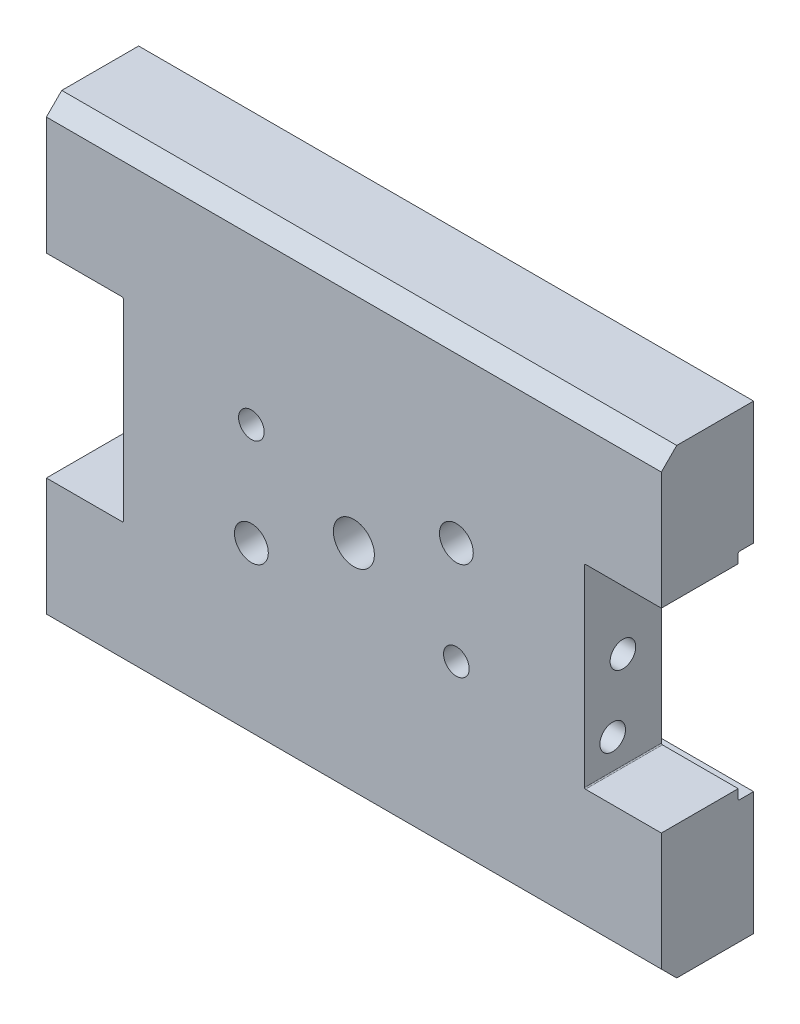
SolidWorks part; units mm, degrees
ref_plane "Piano frontale" through (0, 0, 0) normal (0, 0, 1) x (1, 0, 0)
ref_plane "Piano superiore" through (0, 0, 0) normal (0, 1, 0) x (1, 0, 0)
ref_plane "Piano destro" through (0, 0, 0) normal (1, 0, 0) x (0, 0, -1)
sketch "Schizzo1" plane through (0, 0, 0) normal (0, 0, 1) x (1, 0, 0)
  line L12 (0, 0) -> (0, 62.9746) construction
  line L13 (0, 0) -> (63.3499, 0) construction
  line L14 (-60, 45) -> (60, 45)
  line L15 (60, 45) -> (60, 19)
  line L16 (60, 19) -> (45, 19)
  line L17 (45, 19) -> (45, -19)
  line L18 (45, -19) -> (60, -19)
  line L19 (60, -19) -> (60, -45)
  line L20 (60, -45) -> (-60, -45)
  line L21 (-60, -45) -> (-60, -19)
  line L22 (-60, -19) -> (-45, -19)
  line L23 (-45, -19) -> (-45, 19)
  line L24 (-45, 19) -> (-60, 19)
  line L25 (-60, 19) -> (-60, 45)
  line L26 (-60, 19) -> (-60, -19) construction
  line L27 (60, 19) -> (60, -19) construction
  line L28 (-45, 19) -> (45, 19) construction
  line L29 (-45, -19) -> (45, -19) construction
  dimension "D1" = 120
  dimension "D2" = 90
  dimension "D3" = 38
  dimension "D4" = 90
extrude "Estrusione-Estrusione1" add sketch "Schizzo1" along normal blind 18 contours L22 L23 L24 L25 L14 L15 L16 L17 L18 L19 L20 L21
sketch "Schizzo2" plane through (0, 0, 0) normal (1, 0, 0) x (0, 0, -1)
  line L0 (0, 19) -> (0, -19) construction
  line L1 (0, -21) -> (-3, -21)
  line L2 (0, -21) -> (0, 21)
  line L3 (0, 21) -> (-3, 21)
  line L4 (-3, -21) -> (-3, 21)
  line L5 (0, 0) -> (-50.4811, 0) construction
  dimension "D1" = 3
  dimension "D2" = 42
extrude "Taglio-Estrusione1" cut sketch "Schizzo2" against normal through all and the other way through all
hole_wizard "Foro filettato M6-1" positions "Schizzo3" profile "Schizzo4" tap size "M6" standard "ISO"
sketch "Schizzo3" plane through (45, 0, 0) normal (1, 0, 0) x (0, 0, -1)
  line L0 (-18, -19) -> (-3, 19) construction
  point P0 (-10.5, 0)
cosmetic thread "Filettatura del foro1" parameters "D1"=15, "D2"=6
sketch "Schizzo4" plane through (45, 0, 10.5) normal (0, 1, 0) x (0, 0, -1)
  line L0 (0, 0) -> (0, 21.5022)
  line L1 (0, 21.5022) -> (2.5, 20)
  line L2 (2.5, 20) -> (2.5, 0)
  line L5 (2.5, 0) -> (0, 0)
  line L10 (0, 21.5022) -> (-2.5, 20) construction
  line L11 (0, -6.35) -> (0, 107.95) construction
  dimension "Tap Drill Dia." = 5
  dimension "Tap Drill Depth" = 20
  dimension "Drill Angle" = 118
hole_wizard "Foro Ø8.0 (8)-1" positions "Schizzo5" profile "Schizzo6" hole size "Ø8.0" standard "ISO" end condition through all
sketch "Schizzo5" plane through (0, 0, 18) normal (0, 0, 1) x (1, 0, 0)
  line L0 (45, 0) -> (-45, 0) construction
  line L1 (45, 19) -> (45, -19) construction
  line L2 (-45, -19) -> (-45, 19) construction
  line L4 (0, -45) -> (0, 45) construction
  line L5 (60, -45) -> (-60, -45) construction
  line L6 (-60, 45) -> (60, 45) construction
  point P21 (0, 0)
sketch "Schizzo6" plane through (0, 0, 18) normal (1, 0, 0) x (0, -1, 0)
  line L0 (0, 0) -> (0, 18)
  line L1 (0, 18) -> (4, 18)
  line L2 (4, 18) -> (4, 0)
  line L5 (4, 0) -> (0, 0)
  line L11 (0, -6.35) -> (0, 107.95) construction
  dimension "Thru Hole Dia." = 8
  dimension "Thru Hole Depth" = 18
hole_wizard "Foro Ø5.0 (5)-2" positions "Schizzo7" profile "Schizzo8" hole size "Ø5.0" standard "ISO" end condition through all
sketch "Schizzo7" plane through (0, 0, 18) normal (0, 0, 1) x (1, 0, 0)
  line L0 (20, -10) -> (-20, 10) construction
  line L2 (0, 0) -> (0, 14.5749) construction
  point P0 (20, -10)
  point P2 (-20, 10)
  dimension "D1" = 10
  dimension "D2" = 20
sketch "Schizzo8" plane through (20, -10, 18) normal (1, 0, 0) x (0, -1, 0)
  line L0 (0, 0) -> (0, 18)
  line L1 (0, 18) -> (2.5, 18)
  line L2 (2.5, 18) -> (2.5, 0)
  line L5 (2.5, 0) -> (0, 0)
  line L11 (0, -6.35) -> (0, 107.95) construction
  dimension "Thru Hole Dia." = 5
  dimension "Thru Hole Depth" = 18
hole_wizard "Foro lamato per Vite M6 a testa cilindrica-1" positions "Schizzo9" profile "Schizzo10" counterbore size "M6" standard "ISO" end condition through all
sketch "Schizzo9" plane through (0, 0, 3) normal (0, 0, -1) x (-1, 0, 0)
  line L2 (-20, -10) -> (20, -10) construction
  line L3 (-20, -10) -> (-20, 10) construction
  line L4 (-20, 10) -> (20, 10) construction
  line L5 (20, -10) -> (20, 10) construction
  point P0 (-20, 10)
  point P2 (20, -10)
sketch "Schizzo10" plane through (20, 10, 3) normal (1, 0, 0) x (0, 1, 0)
  line L0 (0, 0) -> (0, 15)
  line L1 (0, 15) -> (3.3, 15)
  line L3 (3.3, 15) -> (3.3, 6.4)
  line L4 (3.3, 6.4) -> (5.5, 6.4)
  line L5 (5.5, 6.4) -> (5.5, 0)
  line L7 (5.5, 0) -> (0, 0)
  line L11 (0, -6.35) -> (0, 107.95) construction
  dimension "Thru Hole Dia." = 6.6
  dimension "Thru Hole Depth" = 15
  dimension "C'Bore Dia." = 11
  dimension "C'Bore Depth" = 6.4
hole_wizard "Foro Ø5.0 (5)-3" positions "Schizzo13" profile "Schizzo14" hole size "Ø5.0" standard "ISO"
sketch "Schizzo13" plane through (45, 0, 0) normal (1, 0, 0) x (0, 0, -1)
  line L0 (-12.5, -13) -> (-8.5, 13) construction
  line L2 (-10.5, 0) -> (-4.8871, 0) construction
  point P0 (-12.5, -13)
  point P2 (-8.5, 13)
  dimension "D1" = 13
  dimension "D2" = 2
sketch "Schizzo14" plane through (45, -13, 12.5) normal (0, 1, 0) x (0, 0, -1)
  line L0 (0, 0) -> (0, 11.5022)
  line L1 (0, 11.5022) -> (2.5, 10)
  line L2 (2.5, 10) -> (2.5, 0)
  line L5 (2.5, 0) -> (0, 0)
  line L10 (0, 11.5022) -> (-2.5, 10) construction
  line L11 (0, -6.35) -> (0, 107.95) construction
  dimension "Hole Dia." = 5
  dimension "Hole Depth" = 10
  dimension "Drill Angle" = 118
chamfer "Smusso1" distance 3 angle 45 2 edges at (0, -45, 18) (0, 45, 18)
fillet "Raccordo1" radius 0.2 6 edges at (-45, -19, 10.5) (-45, 19, 10.5) (45, -19, 10.5) (45, 19, 10.5) (0, 21, 3) (0, -21, 3)
mirror "Specchia1" about plane through (0, 0, 0) normal (1, 0, 0) of "Foro filettato M6-1", "Foro Ø5.0 (5)-3"
cosmetic thread "Filettatura del foro3" parameters "D1"=15, "D2"=6
